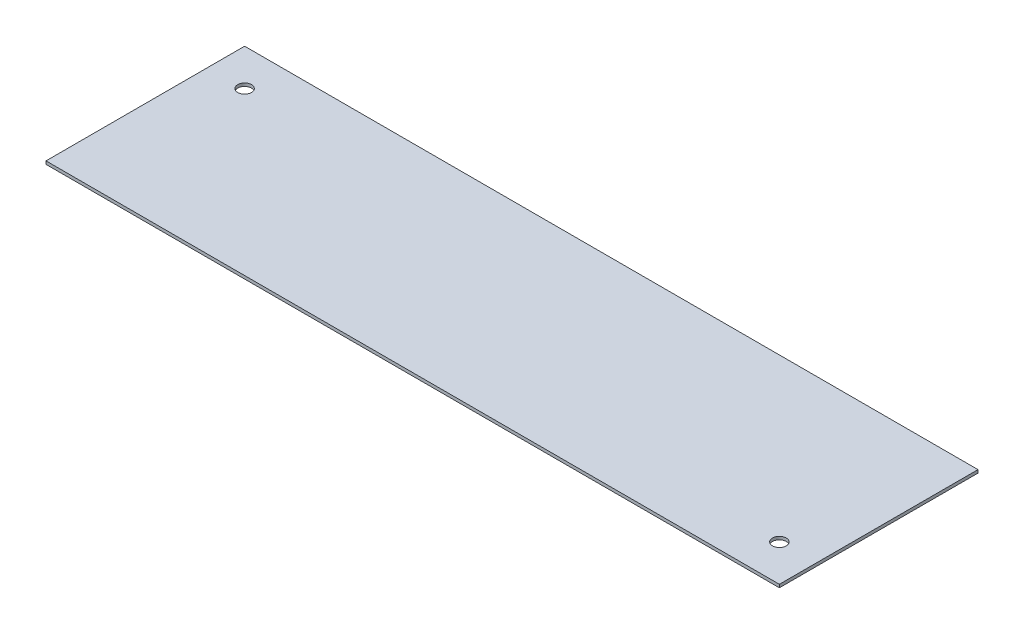
SolidWorks part; units mm, degrees
ref_plane "Front Plane" through (0, 0, 0) normal (0, 0, 1) x (1, 0, 0)
ref_plane "Top Plane" through (0, 0, 0) normal (0, 1, 0) x (1, 0, 0)
ref_plane "Right Plane" through (0, 0, 0) normal (1, 0, 0) x (0, 0, -1)
sketch "Sketch1" plane through (0, 0, 0) normal (0, 1, 0) x (1, 0, 0)
  line L1 (-127.6225, 32.2086) -> (112.3775, 32.2086)
  line L2 (-127.6225, 32.2086) -> (-127.6225, -32.7914)
  line L3 (-127.6225, -32.7914) -> (112.3775, -32.7914)
  line L4 (112.3775, 32.2086) -> (112.3775, -32.7914)
  dimension "D1" = 65
  dimension "D2" = 240
extrude "Boss-Extrude1" add sketch "Sketch1" along normal blind 1
hole_wizard "M4 Clearance Slot1" positions "Sketch2" profile "Sketch3" size "M4" standard "ANSI Metric" slot yes end condition through all
sketch "Sketch2" plane through (0, 1, 0) normal (0, 1, 0) x (1, 0, 0)
  line L0 (112.3775, 32.2086) -> (-127.6225, 32.2086) construction
  line L1 (-127.6225, 32.2086) -> (-127.6225, -32.7914) construction
  line L2 (-127.6225, -32.7914) -> (112.3775, -32.7914) construction
  line L3 (112.3775, -32.7914) -> (112.3775, 32.2086) construction
  point P0 (100.3775, -20.7914)
  point P2 (-115.6225, 20.2086)
  dimension "D1" = 12
  dimension "D2" = 12
  dimension "D3" = 12
  dimension "D4" = 12
sketch "Sketch3" plane through (100.3775, 1, 20.7914) normal (1, 0, 0) x (0, 0, 1)
  line L0 (0, 0) -> (0, 1)
  line L1 (0, 1) -> (2.25, 1)
  line L2 (2.25, 1) -> (2.25, 0)
  line L5 (2.25, 0) -> (0, 0)
  line L11 (0, -6.35) -> (0, 107.95) construction
  dimension "Thru Hole Dia." = 4.5
  dimension "Thru Hole Depth" = 1
